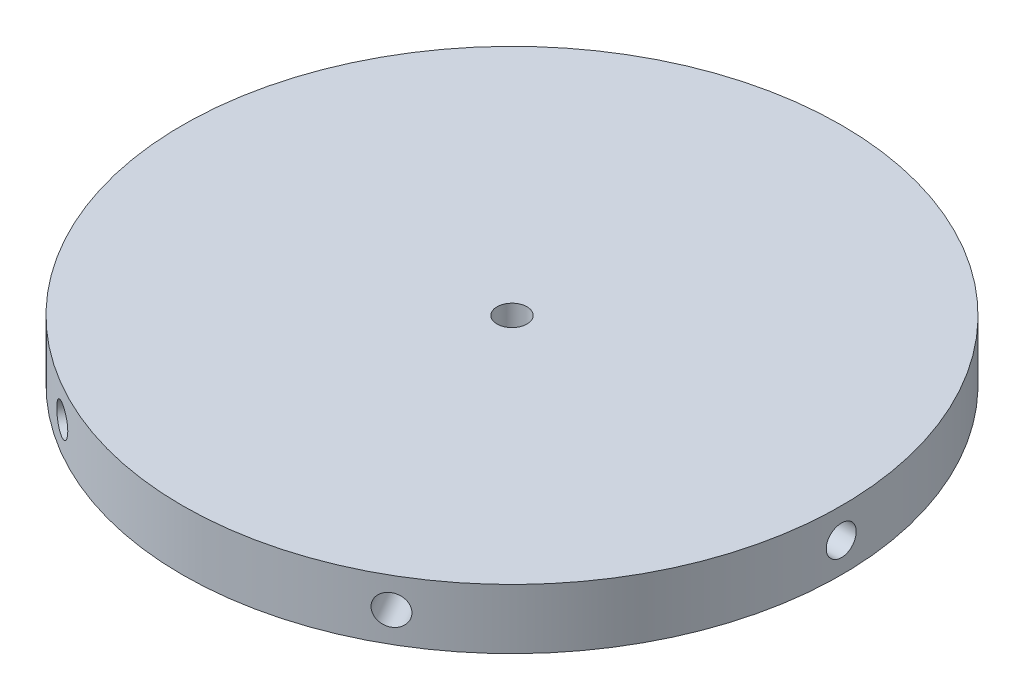
SolidWorks part; units mm, degrees
ref_plane "Front Plane" through (0, 0, 0) normal (0, 0, 1) x (1, 0, 0)
ref_plane "Top Plane" through (0, 0, 0) normal (0, 1, 0) x (1, 0, 0)
ref_plane "Right Plane" through (0, 0, 0) normal (1, 0, 0) x (0, 0, -1)
sketch "Sketch1" plane through (0, 0, 0) normal (0, 1, 0) x (1, 0, 0)
  circle A0 centre (0, 0) radius 69.85
  circle A1 centre (0, 0) radius 3.175
  dimension "D1" = 139.7
  dimension "D2" = 6.35
extrude "Boss-Extrude1" add sketch "Sketch1" along normal blind 12.7
ref_plane "Plane1" through (73.914, 0, 0) normal (1, 0, 0) x (0, 0, -1)
sketch "Sketch2" plane through (73.914, 0, 0) normal (1, 0, 0) x (0, 0, -1)
  line L0 (0, 0) -> (0, 12.7) construction
  line L1 (69.85, 12.7) -> (-69.85, 12.7) construction
  circle A0 centre (0, 6.35) radius 3.175
  dimension "D1" = 6.35
extrude "Cut-Extrude1" cut sketch "Sketch2" against normal blind 12.7
pattern_circular "CirPattern1" count 6 over 360 about axis through (0, 0, 0) along (0, 1, 0) of "Cut-Extrude1"
